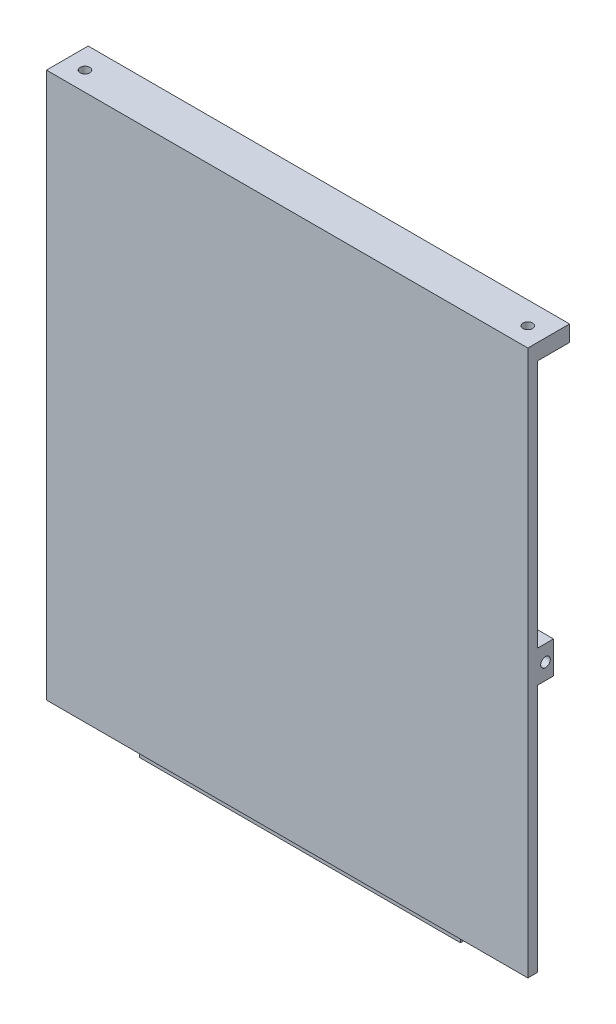
SolidWorks part; units mm, degrees
ref_plane "Front Plane" through (0, 0, 0) normal (0, 0, 1) x (1, 0, 0)
ref_plane "Top Plane" through (0, 0, 0) normal (0, 1, 0) x (1, 0, 0)
ref_plane "Right Plane" through (0, 0, 0) normal (1, 0, 0) x (0, 0, -1)
sketch "Sketch1" plane through (0, 0, 0) normal (0, 1, 0) x (1, 0, 0)
  line L1 (-75, 1.5) -> (75, 1.5)
  line L2 (-75, 1.5) -> (-75, -1.5)
  line L3 (-75, -1.5) -> (75, -1.5)
  line L4 (75, 1.5) -> (75, -1.5)
  line L5 (-75, 1.5) -> (75, -1.5) construction
  line L6 (-75, -1.5) -> (75, 1.5) construction
  point P0 (0, 0)
  dimension "D1" = 150
  dimension "3" = 3
extrude "Boss-Extrude1" add sketch "Sketch1" along normal blind 170
sketch "Sketch2" plane through (0, 0, -1.5) normal (0, 0, -1) x (-1, 0, 0)
  line L0 (75, 170) -> (75, 0) construction
  line L1 (-75, 170) -> (75, 170)
  line L2 (-75, 170) -> (-75, 165)
  line L3 (-75, 165) -> (75, 165)
  line L4 (75, 170) -> (75, 165)
  dimension "D1" = 5
extrude "Boss-Extrude2" add sketch "Sketch2" along normal blind 10
sketch "Sketch3" plane through (0, 0, -1.5) normal (0, 0, -1) x (-1, 0, 0)
  line L0 (0, 0) -> (0, 35.1313) construction
  line L1 (-75, 0) -> (75, 0) construction
  line L3 (-50, 3) -> (50, 3)
  line L4 (-50, 3) -> (-50, 0)
  line L5 (-50, 0) -> (50, 0)
  line L6 (50, 3) -> (50, 0)
  line L7 (-50, 3) -> (50, 0) construction
  line L8 (-50, 0) -> (50, 3) construction
  point P4 (0, 1.5)
  dimension "D1" = 3
  dimension "D2" = 1.5
  dimension "D3" = 100
extrude "Boss-Extrude3" add sketch "Sketch3" along normal blind 3
sketch "Sketch4" plane through (0, 0, 0) normal (0, -1, 0) x (1, 0, 0)
  line L1 (50, -4.5) -> (-50, -4.5)
  line L2 (50, -4.5) -> (50, -1.5)
  line L3 (50, -1.5) -> (-50, -1.5)
  line L4 (-50, -4.5) -> (-50, -1.5)
extrude "Boss-Extrude4" add sketch "Sketch4" along normal blind 5
sketch "Sketch5" plane through (0, 170, 0) normal (0, 1, 0) x (1, 0, 0)
  line L0 (-75, -1.5) -> (75, -1.5) construction
  line L2 (75, -1.5) -> (75, 11.5) construction
  line L3 (0, 11.5) -> (0, -0.9352) construction
  line L4 (-75, 11.5) -> (75, 11.5) construction
  circle A0 centre (69, 4.5) radius 1.5
  circle A1 centre (-69, 4.5) radius 1.5
  dimension "D3" = 3
  dimension "D1" = 6
  dimension "D2" = 6
extrude "Cut-Extrude1" cut sketch "Sketch5" against normal through all
sketch "Sketch6" plane through (75, 0, 0) normal (1, 0, 0) x (0, 0, -1)
  line L0 (1.5, 82.5) -> (-1.5, 82.5) construction
  line L1 (1.5, 165) -> (1.5, 0) construction
  line L2 (-1.5, 170) -> (-1.5, 0) construction
  line L4 (-1.5, 77.5) -> (6.5, 77.5)
  line L5 (-1.5, 77.5) -> (-1.5, 87.5)
  line L6 (-1.5, 87.5) -> (6.5, 87.5)
  line L7 (6.5, 77.5) -> (6.5, 87.5)
  point P10 (0, 82.5)
  dimension "D1" = 5
  dimension "D2" = 5
  dimension "D3" = 8
extrude "Boss-Extrude5" add sketch "Sketch6" against normal blind 5
sketch "Sketch8" plane through (-75, 0, 0) normal (-1, 0, 0) x (0, 0, 1)
  line L0 (-1.5, 82.5) -> (1.5, 82.5) construction
  line L1 (-1.5, 165) -> (-1.5, 0) construction
  line L2 (1.5, 170) -> (1.5, 0) construction
  line L4 (1.5, 77.5) -> (-6.5, 77.5)
  line L5 (1.5, 77.5) -> (1.5, 87.5)
  line L6 (1.5, 87.5) -> (-6.5, 87.5)
  line L7 (-6.5, 77.5) -> (-6.5, 87.5)
  dimension "D1" = 5
  dimension "D2" = 5
  dimension "D3" = 8
extrude "Boss-Extrude6" add sketch "Sketch8" against normal blind 5
sketch "Sketch9" plane through (-75, 0, 0) normal (-1, 0, 0) x (0, 0, 1)
  line L0 (-6.5, 82.5) -> (1.5, 82.5) construction
  line L1 (-6.5, 87.5) -> (-6.5, 77.5) construction
  line L2 (1.5, 170) -> (1.5, 0) construction
  circle A0 centre (-4, 82.5) radius 1.5
  dimension "D1" = 3
  dimension "D2" = 2.5
extrude "Cut-Extrude2" cut sketch "Sketch9" against normal through all
sketch "Sketch10" plane through (0, 0, -1.5) normal (0, 0, 1) x (1, 0, 0)
  line L8 (50, 0) -> (-50, 0)
  line L9 (-50, 0) -> (-50, -5)
  line L10 (-50, -5) -> (50, -5)
  line L11 (50, -5) -> (50, 0)
  line L12 (50, 0) -> (-50, 0)
  line L13 (-50, 0) -> (-50, -5)
  line L14 (-50, -5) -> (50, -5)
  line L15 (50, -5) -> (50, 0)
  dimension "D1" = 0
extrude "Cut-Extrude3" cut sketch "Sketch10" against normal blind 1
